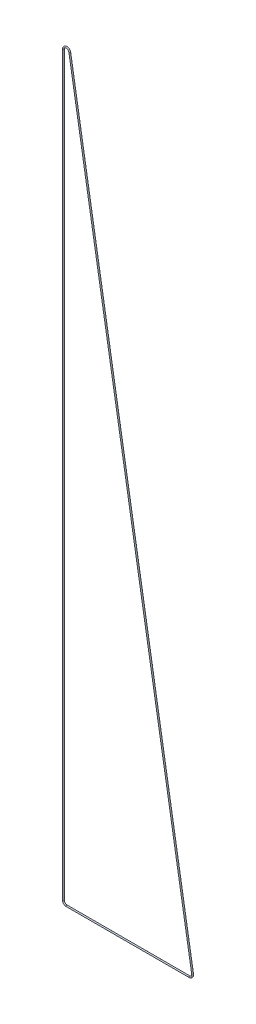
SolidWorks part; units mm, degrees
ref_plane "Alzado" through (0, 0, 0) normal (0, 0, 1) x (1, 0, 0)
ref_plane "Planta" through (0, 0, 0) normal (0, 1, 0) x (1, 0, 0)
ref_plane "Vista lateral" through (0, 0, 0) normal (1, 0, 0) x (0, 0, -1)
sketch "Croquis1" plane through (0, 0, 0) normal (0, 0, 1) x (1, 0, 0)
  line L0 (0, 10) -> (0, 2279.1724)
  line L1 (19.8639, 2280.8164) -> (398.0593, 11.644)
  line L2 (388.1954, 0) -> (10, 0)
  arc A0 (0, 2279.1724) -> (19.8639, 2280.8164) centre (10, 2279.1724) cw
  arc A1 (0, 10) -> (10, 0) centre (10, 10) ccw
  arc A2 (398.0593, 11.644) -> (388.1954, 0) centre (388.1954, 10) cw
  point P6 (0, 2400)
  point P9 (0, 0)
  point P12 (400, 0)
  dimension "D3" = 10
  dimension "D4" = 10
  dimension "D5" = 10
  dimension "D1" = 2400
  dimension "D2" = 400
ref_plane "Plano1" through (10, 0, 0) normal (1, 0, 0) x (0, 0, -1)
sketch "Croquis2" plane through (10, 0, 0) normal (1, 0, 0) x (0, 0, -1)
  circle A0 centre (0, 0) radius 2
  dimension "D1" = 4
sweep "Barrer1" add profiles "Croquis2" path "Croquis1"
